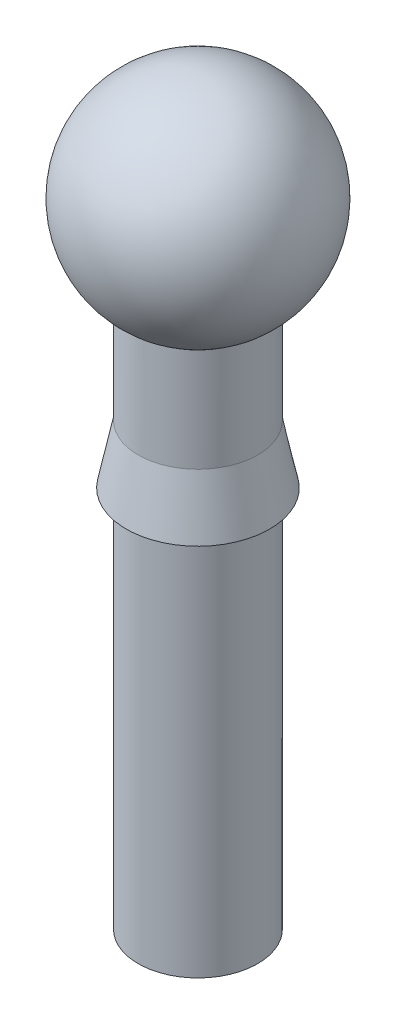
SolidWorks part; units mm, degrees
ref_plane "前视基准面" through (0, 0, 0) normal (0, 0, 1) x (1, 0, 0)
ref_plane "上视基准面" through (0, 0, 0) normal (0, 1, 0) x (1, 0, 0)
ref_plane "右视基准面" through (0, 0, 0) normal (1, 0, 0) x (0, 0, -1)
other "Configuration Table"
sketch "草图1" plane through (0, 0, 0) normal (0, 0, 1) x (1, 0, 0)
  line L0 (0, 0) -> (0, 34.268) construction
  line L1 (2.5, 22.7583) -> (2.5, 18.4348)
  line L2 (2.5, 18.4348) -> (3, 16)
  line L3 (3, 16) -> (2.5, 16)
  line L4 (2.5, 16) -> (2.5, 0)
  line L5 (2.5, 0) -> (0, 0)
  line L6 (0, 0) -> (0, 31) construction
  line L7 (0, 0) -> (0, 31)
  arc A0 (2.5, 22.7583) -> (0, 31) centre (0, 26.5) ccw
  dimension "D1" = 9
  dimension "D4" = 10.5
  dimension "D5" = 26.5
  dimension "D2" = 2.5
  dimension "D3" = 3
  dimension "D6" = 2.5
revolve "旋转3" add sketch "草图1" angle 360 about L6
